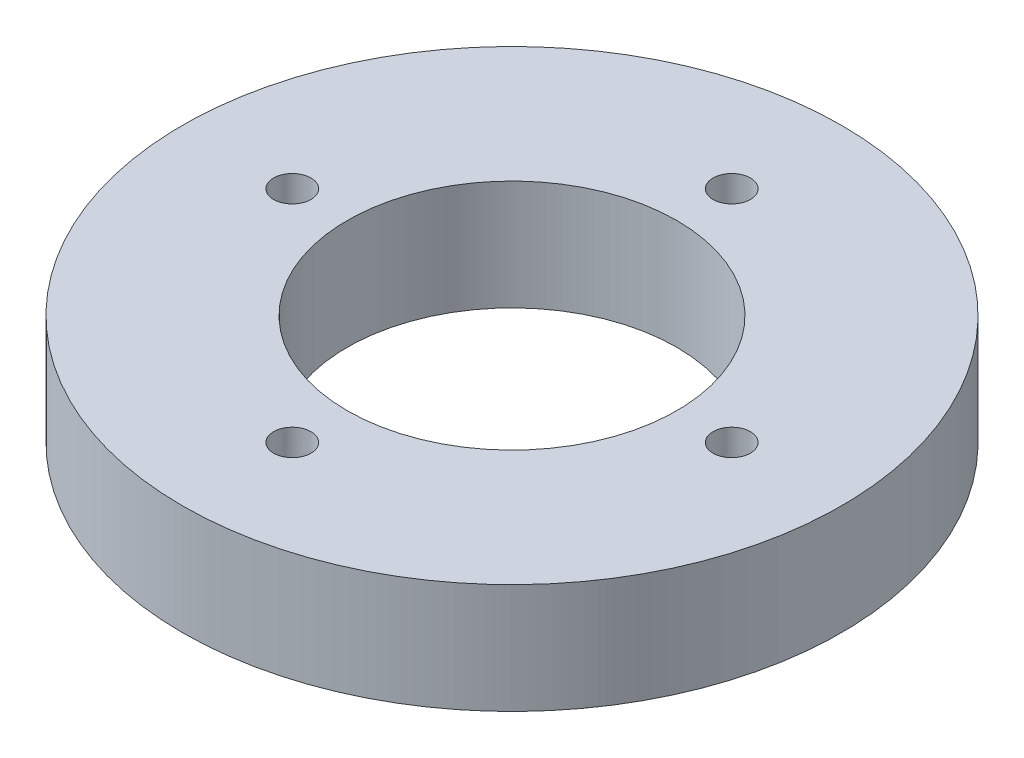
SolidWorks part; units mm, degrees
material "ESUN PLA +"
ref_plane "Front Plane" through (0, 0, 0) normal (0, 0, 1) x (1, 0, 0)
ref_plane "Top Plane" through (0, 0, 0) normal (0, 1, 0) x (1, 0, 0)
ref_plane "Right Plane" through (0, 0, 0) normal (1, 0, 0) x (0, 0, -1)
sketch "Sketch1" plane through (0, 0, 0) normal (0, 1, 0) x (1, 0, 0)
  circle A0 centre (0, 0) radius 30
  circle A1 centre (0, 0) radius 15
  dimension "D1" = 60
  dimension "D2" = 30
extrude "Boss-Extrude1" add sketch "Sketch1" along normal blind 10
sketch "Sketch2" plane through (0, 10, 0) normal (0, 1, 0) x (1, 0, 0)
  circle A0 centre (0, -20) radius 1.7
  point P2 (0, 0)
  dimension "D1" = 3.4
  dimension "D2" = 20
extrude "Cut-Extrude1" cut sketch "Sketch2" against normal through all
sketch "Sketch3" plane through (0, 0, 0) normal (0, -1, 0) x (1, 0, 0)
  line L1 (3.4641, 20) -> (1.7321, 23)
  line L2 (1.7321, 23) -> (-1.7321, 23)
  line L3 (-1.7321, 23) -> (-3.4641, 20)
  line L4 (-3.4641, 20) -> (-1.7321, 17)
  line L5 (-1.7321, 17) -> (1.7321, 17)
  line L6 (1.7321, 17) -> (3.4641, 20)
  circle A0 centre (0, 20) radius 3 construction
  dimension "D1" = 6
extrude "Cut-Extrude2" cut sketch "Sketch3" against normal blind 3
pattern_circular "CirPattern1" count 4 over 360 about axis through (0, 0, 0) along (0, 1, 0) of "Cut-Extrude1", "Cut-Extrude2"
